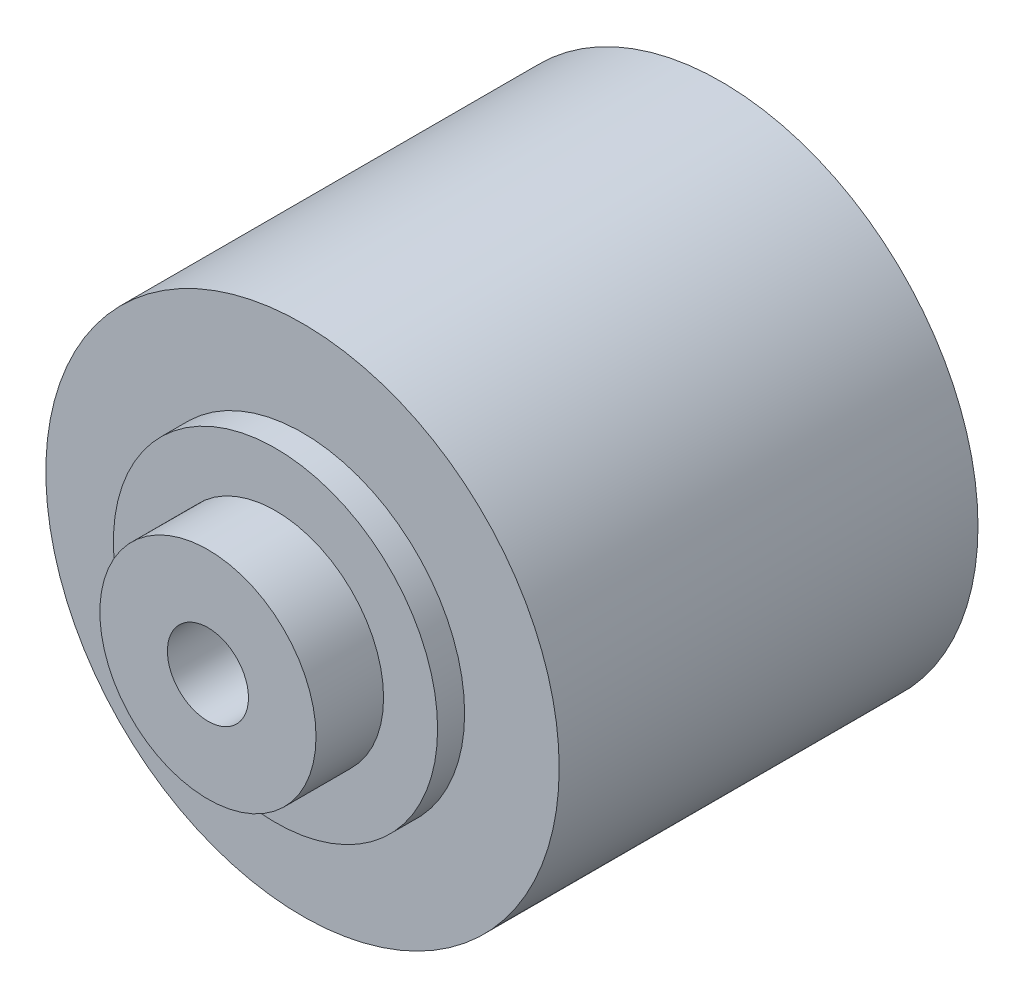
SolidWorks part; units mm, degrees
ref_plane "前视基准面" through (0, 0, 0) normal (0, 0, 1) x (1, 0, 0)
ref_plane "上视基准面" through (0, 0, 0) normal (0, 1, 0) x (1, 0, 0)
ref_plane "右视基准面" through (0, 0, 0) normal (1, 0, 0) x (0, 0, -1)
sketch "草图1" plane through (0, 0, 0) normal (0, 0, 1) x (1, 0, 0)
  circle A0 centre (0, 0) radius 19
  dimension "D1" = 38
extrude "凸台-拉伸1" add sketch "草图1" along normal blind 31
sketch "草图2" plane through (0, 0, 31) normal (0, 0, 1) x (1, 0, 0)
  circle A0 centre (0, 0) radius 8
  dimension "D1" = 16
extrude "凸台-拉伸2" add sketch "草图2" along normal blind 7
sketch "草图3" plane through (0, 0, 38) normal (0, 0, 1) x (1, 0, 0)
  circle A0 centre (0, 0) radius 3
  dimension "D1" = 6
extrude "切除-拉伸1" cut sketch "草图3" against normal through all
sketch "草图4" plane through (0, 0, 31) normal (0, 0, 1) x (1, 0, 0)
  circle A0 centre (0, 0) radius 12
  dimension "D1" = 24
extrude "凸台-拉伸3" add sketch "草图4" along normal blind 2
sketch "草图5" plane through (0, 0, 0) normal (0, 0, -1) x (-1, 0, 0)
  circle A0 centre (0, 0) radius 10
  circle A1 centre (0, 0) radius 3
  dimension "D1" = 20
  dimension "D2" = 6
extrude "凸台-拉伸4" add sketch "草图5" along normal blind 1
